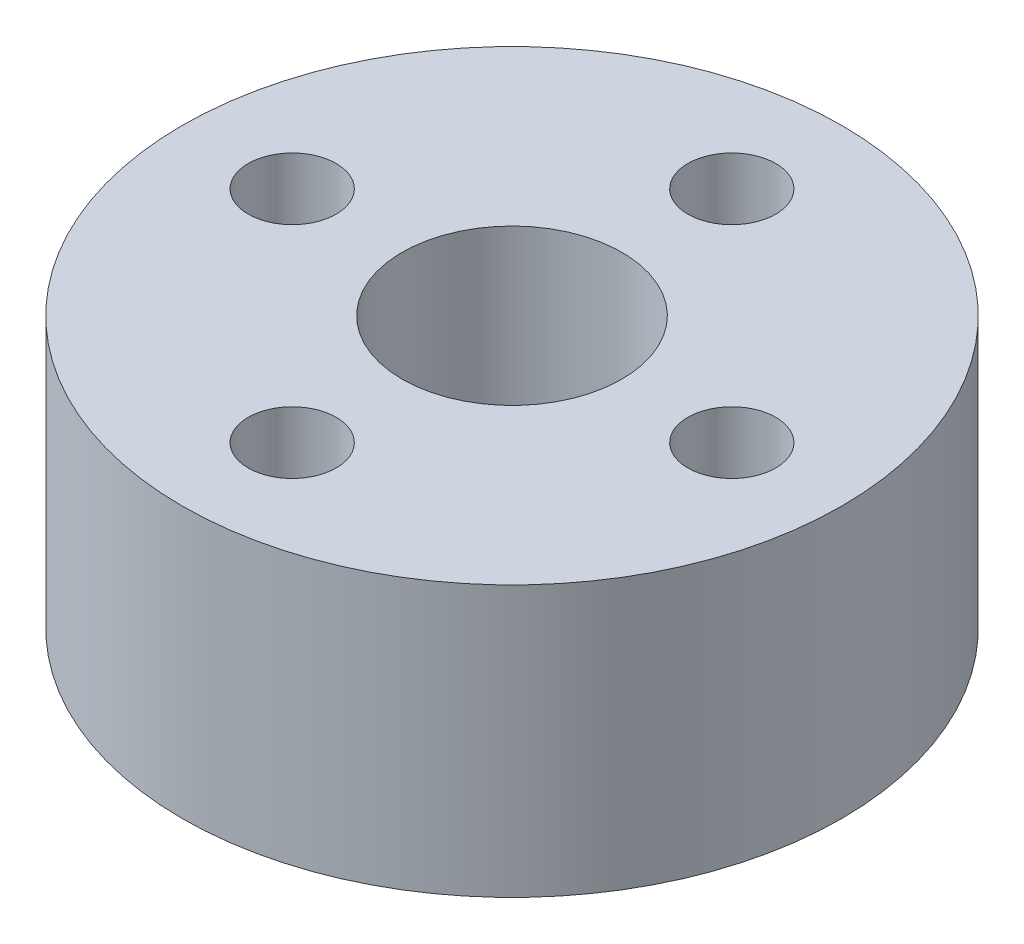
SolidWorks part; units mm, degrees
ref_plane "Front Plane" through (0, 0, 0) normal (0, 0, 1) x (1, 0, 0)
ref_plane "Top Plane" through (0, 0, 0) normal (0, 1, 0) x (1, 0, 0)
ref_plane "Right Plane" through (0, 0, 0) normal (1, 0, 0) x (0, 0, -1)
sketch "Sketch1" plane through (0, 0, 0) normal (0, 1, 0) x (1, 0, 0)
  circle A0 centre (0, 0) radius 30
extrude "Boss-Extrude1" add sketch "Sketch1" along normal blind 50
sketch "Sketch2" plane through (0, 0, 0) normal (0, -1, 0) x (-1, 0, 0)
  circle A0 centre (0, 0) radius 75
extrude "Boss-Extrude2" add sketch "Sketch2" against normal blind 50 contours A0
sketch "Sketch3" plane through (0, 50, 0) normal (0, 1, 0) x (1, 0, 0)
  circle A0 centre (0, 0) radius 25
  circle A2 centre (0, -50) radius 10
  circle A3 centre (50, 0) radius 10
  circle A4 centre (0, 50) radius 10
  circle A5 centre (-50, 0) radius 10
extrude "Cut-Extrude1" cut sketch "Sketch3" against normal blind 50
sketch "Sketch5" plane through (0, 0, 0) normal (0, -1, 0) x (-1, 0, 0)
  circle A0 centre (0, 0) radius 75
  circle A1 centre (0, 0) radius 30
extrude "Boss-Extrude4" add sketch "Sketch5" along normal blind 11.5686
